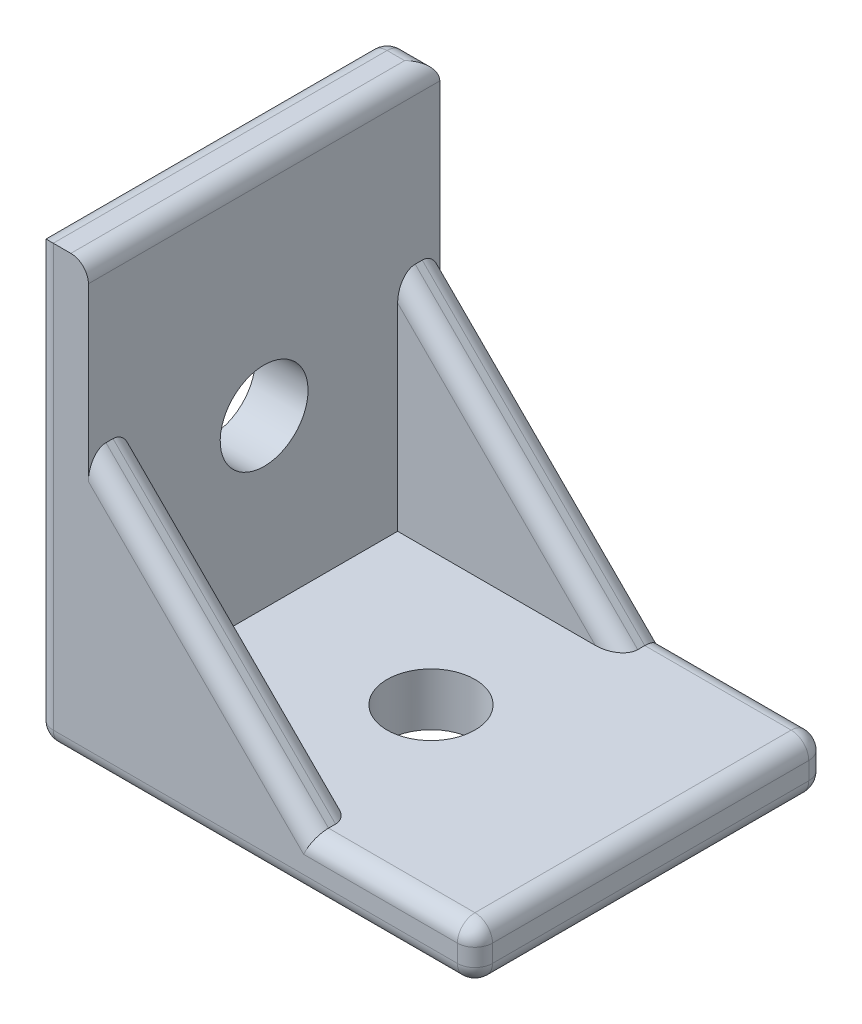
SolidWorks part; units mm, degrees
ref_plane "Front Plane" through (0, 0, 0) normal (0, 0, 1) x (1, 0, 0)
ref_plane "Top Plane" through (0, 0, 0) normal (0, 1, 0) x (1, 0, 0)
ref_plane "Right Plane" through (0, 0, 0) normal (1, 0, 0) x (0, 0, -1)
sketch "Sketch1" plane through (0, 0, 0) normal (0, 0, 1) x (1, 0, 0)
  line L1 (-12.5, 12.5) -> (12.5, 12.5)
  line L2 (-12.5, 12.5) -> (-12.5, -12.5)
  line L3 (-12.5, -12.5) -> (12.5, -12.5)
  line L4 (12.5, 12.5) -> (12.5, -12.5)
  line L5 (-12.5, 12.5) -> (12.5, -12.5) construction
  line L6 (-12.5, -12.5) -> (12.5, 12.5) construction
  point P0 (0, 0)
  dimension "D1" = 25
extrude "Boss-Extrude1" add sketch "Sketch1" along normal blind 20
sketch "Sketch2" plane through (0, 0, 20) normal (0, 0, 1) x (1, 0, 0)
  line L1 (12.5, 12.5) -> (-9.5, 12.5)
  line L2 (12.5, 12.5) -> (12.5, -9.5)
  line L3 (12.5, -9.5) -> (-9.5, -9.5)
  line L4 (-9.5, 12.5) -> (-9.5, -9.5)
  line L5 (-12.5, -12.5) -> (12.5, -12.5) construction
  dimension "D1" = 3
extrude "Cut-Extrude3" cut sketch "Sketch2" against normal blind 15.2 from offset 2.4 offset against normal yes
sketch "Sketch3" plane through (0, 0, 20) normal (0, 0, 1) x (1, 0, 0)
  line L0 (-9.5, 3.1667) -> (3.1667, -9.5)
  line L1 (12.5, 12.5) -> (-9.5, 12.5)
  line L2 (12.5, 12.5) -> (12.5, -9.5)
  line L3 (12.5, -9.5) -> (3.1667, -9.5)
  line L4 (-9.5, 12.5) -> (-9.5, 3.1667)
  dimension "D1" = 22
  dimension "D2" = 9.3333
  dimension "D3" = 9.3333
extrude "Cut-Extrude4" cut sketch "Sketch3" against normal through all contours L1 L4 L0 L3 L2
fillet "Fillet1" radius 1 18 edges at (12.5, -11, 0) (7.8333, -9.5, 0) (0, -12.5, 0) (-12.5, -12.5, 10) (-12.5, 0, 0) (-11, 12.5, 0) (-9.5, 12.5, 10) (-12.5, 12.5, 10) (-12.5, 0, 20) (0, -12.5, 20) (12.5, -11, 20) (12.5, -12.5, 10) (12.5, -9.5, 10) (7.8333, -9.5, 20) (-3.1667, -3.1667, 17.6) (-3.1667, -3.1667, 20) (-3.1667, -3.1667, 0) (-3.1667, -3.1667, 2.4)
sketch "Sketch5" plane through (0, -12.5, 0) normal (0, -1, 0) x (1, 0, 0)
  circle A0 centre (0, 10) radius 2.5
  point P0 (0, 10)
  dimension "D1" = 5
extrude "Cut-Extrude5" cut sketch "Sketch5" against normal through all
sketch "Sketch6" plane through (-12.5, 0, 0) normal (-1, 0, 0) x (0, 0, 1)
  circle A0 centre (10, 0) radius 2.5
  point P0 (10, 0)
  dimension "D1" = 5
extrude "Cut-Extrude6" cut sketch "Sketch6" against normal through all
